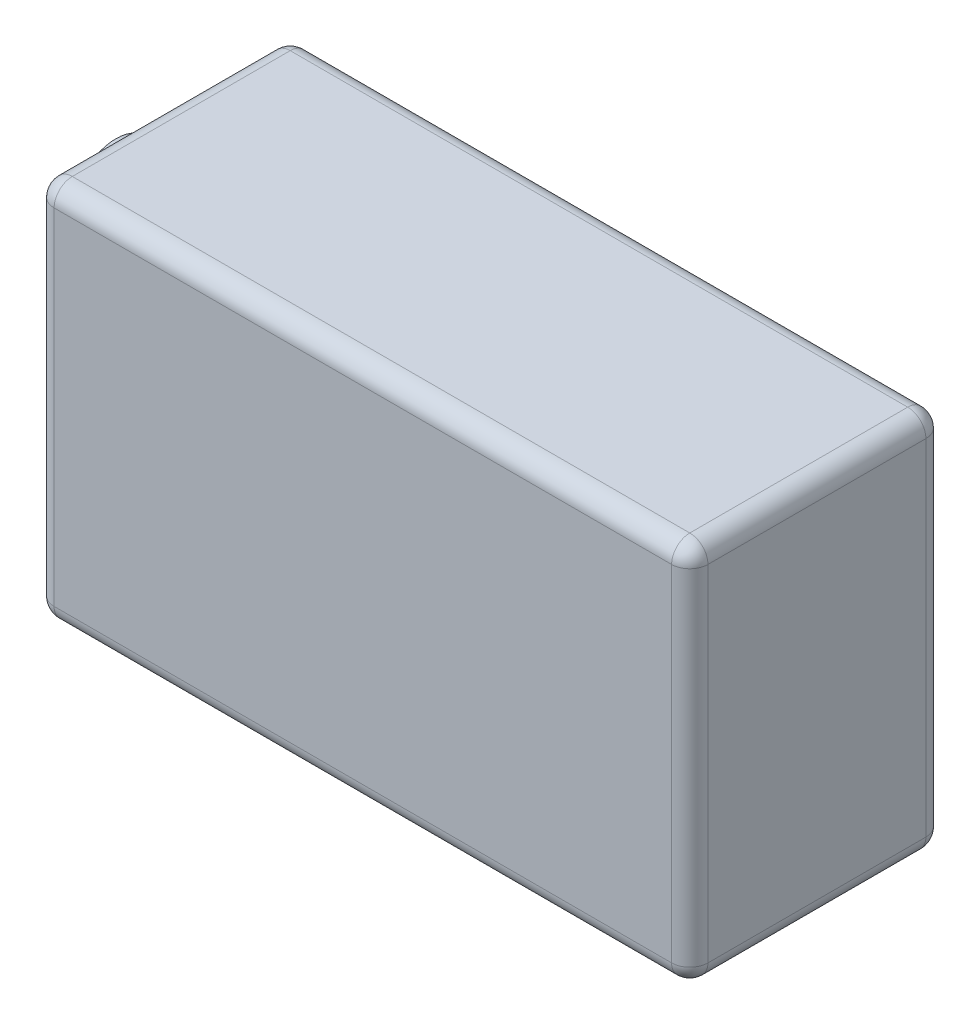
SolidWorks part; units mm, degrees
ref_plane "Front Plane" through (0, 0, 0) normal (0, 0, 1) x (1, 0, 0)
ref_plane "Top Plane" through (0, 0, 0) normal (0, 1, 0) x (1, 0, 0)
ref_plane "Right Plane" through (0, 0, 0) normal (1, 0, 0) x (0, 0, -1)
sketch "Sketch1" plane through (0, 0, 0) normal (0, 0, 1) x (1, 0, 0)
  line L1 (-22.86, 13.335) -> (22.86, 13.335)
  line L2 (-22.86, 13.335) -> (-22.86, -13.335)
  line L3 (-22.86, -13.335) -> (22.86, -13.335)
  line L4 (22.86, 13.335) -> (22.86, -13.335)
  line L5 (-22.86, 13.335) -> (22.86, -13.335) construction
  line L6 (-22.86, -13.335) -> (22.86, 13.335) construction
  point P0 (0, 0)
  dimension "D1" = 26.67
  dimension "D2" = 45.72
extrude "Boss-Extrude1" add sketch "Sketch1" along normal blind 17.78
fillet "Fillet1" radius 1.27 12 edges at (-22.86, 0, 17.78) (-22.86, -13.335, 8.89) (-22.86, 0, 0) (-22.86, 13.335, 8.89) (22.86, 13.335, 8.89) (22.86, 0, 0) (22.86, -13.335, 8.89) (22.86, 0, 17.78) (0, -13.335, 17.78) (0, -13.335, 0) (0, 13.335, 0) (0, 13.335, 17.78)
sketch "Sketch2" plane through (-22.86, 0, 0) normal (-1, 0, 0) x (0, 0, 1)
  line L0 (1.27, 13.335) -> (16.51, 13.335) construction
  circle A0 centre (8.89, 6.5405) radius 2.9845
  circle A1 centre (8.89, -5.8801) radius 4.0005
  dimension "D1" = 3.81
  dimension "D2" = 5.969
  dimension "D3" = 5.4356
  dimension "D4" = 8.001
extrude "Boss-Extrude2" add sketch "Sketch2" along normal blind 3.302
